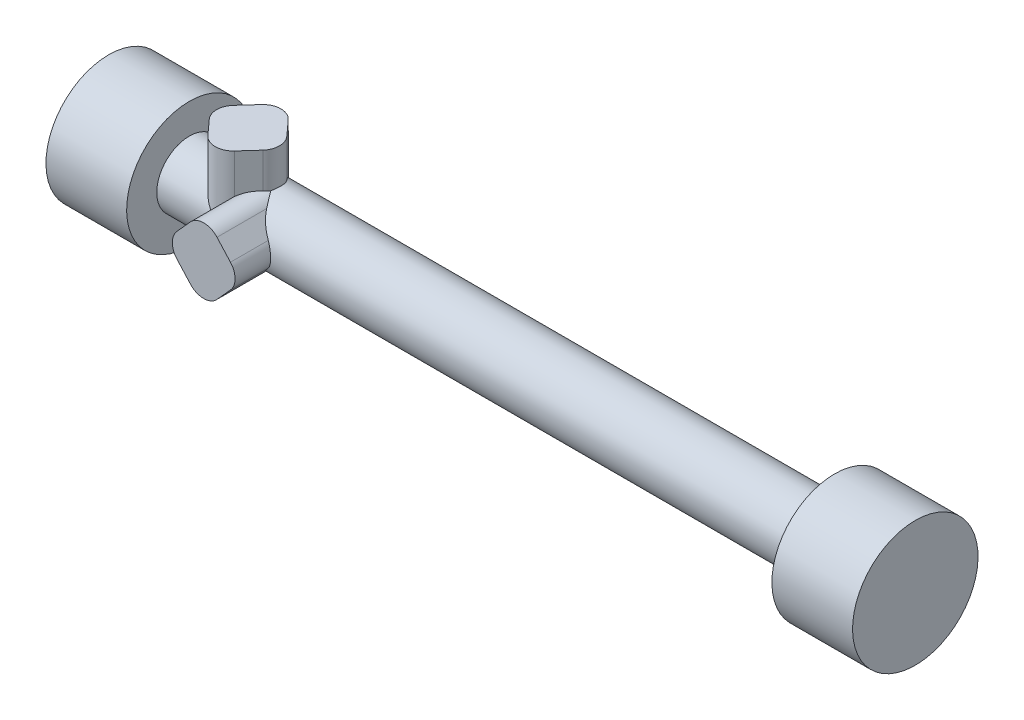
SolidWorks part; units mm, degrees
ref_plane "Alzado" through (0, 0, 0) normal (0, 0, 1) x (1, 0, 0)
ref_plane "Planta" through (0, 0, 0) normal (0, 1, 0) x (1, 0, 0)
ref_plane "Vista lateral" through (0, 0, 0) normal (1, 0, 0) x (0, 0, -1)
sketch "Sketch1" plane through (0, 0, 0) normal (0, 0, 1) x (1, 0, 0)
  line L0 (-41.4469, 0) -> (-41.4469, 35)
  line L1 (55, 0) -> (-55, 0) construction
  line L2 (-41.4469, 35) -> (3.5531, 35)
  line L3 (3.5531, 35) -> (3.5531, 18.2)
  line L10 (363.5531, 35) -> (408.5531, 35)
  line L11 (408.5531, 35) -> (408.5531, 0)
  line L12 (408.5531, 0) -> (-41.4469, 0)
  line L13 (3.5531, 18.2) -> (363.5531, 18.2)
  line L14 (363.5531, 35) -> (363.5531, 18.2)
  dimension "D1" = 35
  dimension "D2" = 18.2
  dimension "D3" = 45
  dimension "D4" = 360
  dimension "D5" = 35
  dimension "D6" = 45
revolve "Revolve1" add sketch "Sketch1" angle 360 about L12
sketch "Sketch2" plane through (0, 0, 0) normal (0, 0, 1) x (1, 0, 0)
  line L0 (34.6276, 6.7108) -> (42.1393, 15.0095)
  line L1 (38.5, 0) -> (-38.5, 0) construction
  line L3 (56.967, 15.0095) -> (64.4787, 6.7108)
  line L4 (64.4787, -6.7108) -> (56.967, -15.0095)
  line L6 (42.1393, -15.0095) -> (34.6276, -6.7108)
  line L7 (3.5531, -35) -> (3.5531, 35) construction
  line L8 (363.5531, 18.2) -> (3.5531, 18.2) construction
  line L9 (3.5531, -18.2) -> (363.5531, -18.2) construction
  arc A0 (56.967, 15.0095) -> (42.1393, 15.0095) centre (49.5531, 8.2987) ccw
  arc A1 (56.967, -15.0095) -> (42.1393, -15.0095) centre (49.5531, -8.2987) cw
  arc A2 (34.6276, -6.7108) -> (34.6276, 6.7108) centre (42.0414, 0) cw
  arc A3 (64.4787, -6.7108) -> (64.4787, 6.7108) centre (57.0648, 0) ccw
  point P4 (49.5531, 26.4683)
  point P9 (49.5531, -27.6748)
  point P16 (49.5531, 23.2)
  point P19 (49.5531, -23.2)
  point P22 (28.5531, 0)
  point P25 (70.5531, 0)
  dimension "D7" = 10
  dimension "D8" = 10
  dimension "D9" = 10
  dimension "D10" = 10
  dimension "D1" = 25
  dimension "D2" = 42
  dimension "D3" = 46
  dimension "D4" = 46
  dimension "D5" = 5
  dimension "D6" = 5
extrude "Boss-Extrude1" add sketch "Sketch2" along normal blind 38
sketch "Sketch4" plane through (0, 0, 0) normal (0, 1, 0) x (1, 0, 0)
  line L0 (20.7856, 7.2973) -> (28.2973, 15.596)
  line L1 (43.125, 15.596) -> (50.6367, 7.2973)
  line L2 (50.6367, -6.1243) -> (43.125, -14.4229)
  line L3 (28.2973, -14.4229) -> (20.7856, -6.1243)
  arc A0 (43.125, 15.596) -> (28.2973, 15.596) centre (35.7111, 8.8852) ccw
  arc A1 (43.125, -14.4229) -> (28.2973, -14.4229) centre (35.7111, -7.7121) cw
  arc A2 (20.7856, -6.1243) -> (20.7856, 7.2973) centre (28.1994, 0.5865) cw
  arc A3 (50.6367, -6.1243) -> (50.6367, 7.2973) centre (43.2229, 0.5865) ccw
  dimension "D1" = 10
  dimension "D2" = 10
  dimension "D3" = 10
  dimension "D4" = 10
extrude "Boss-Extrude2" add sketch "Sketch4" along normal blind 38
